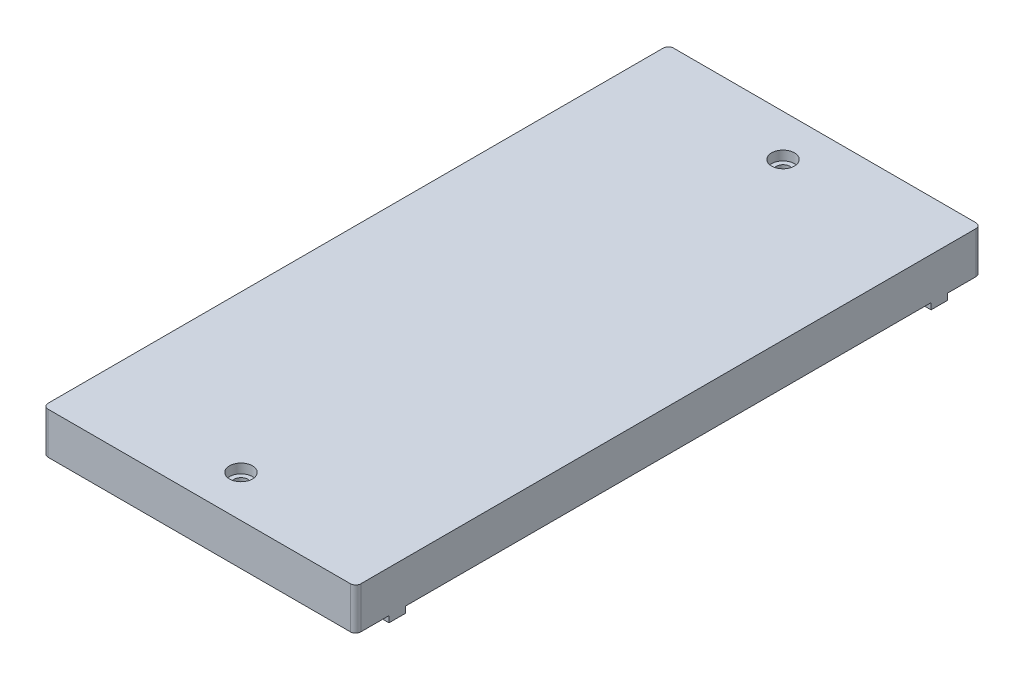
SolidWorks part; units mm, degrees
material "5052-H32"
ref_plane "Front Plane" through (0, 0, 0) normal (0, 0, 1) x (1, 0, 0)
ref_plane "Top Plane" through (0, 0, 0) normal (0, 1, 0) x (1, 0, 0)
ref_plane "Right Plane" through (0, 0, 0) normal (1, 0, 0) x (0, 0, -1)
sketch "Sketch1" plane through (0, 0, 0) normal (0, 1, 0) x (1, 0, 0)
  line L1 (75, -150) -> (-75, -150)
  line L2 (75, -150) -> (75, 150)
  line L3 (75, 150) -> (-75, 150)
  line L4 (-75, -150) -> (-75, 150)
  line L5 (75, -150) -> (-75, 150) construction
  line L6 (75, 150) -> (-75, -150) construction
  point P0 (0, 0)
  dimension "D1" = 150
  dimension "D2" = 300
extrude "Boss-Extrude1" add sketch "Sketch1" along normal blind 20
sketch "Sketch2" plane through (0, 0, 0) normal (0, 1, 0) x (1, 0, 0)
  line L0 (-75, 150) -> (-75, -150) construction
  line L1 (-75, -134) -> (75, -134)
  line L2 (-75, -134) -> (-75, -126)
  line L3 (-75, -126) -> (75, -126)
  line L4 (75, -134) -> (75, -126)
  line L5 (75, -150) -> (75, 150) construction
  line L7 (75, 134) -> (-75, 134)
  line L8 (75, 134) -> (75, 126)
  line L9 (75, 126) -> (-75, 126)
  line L10 (-75, 134) -> (-75, 126)
  point P12 (-75, -130)
  point P14 (-75, 130)
  dimension "D1" = 8
  dimension "D2" = 130
  dimension "D3" = 260
extrude "Boss-Extrude2" add sketch "Sketch2" against normal blind 3
hole_wizard "CBORE for M6 Hex Socket Thin Head Cap Screw1" positions "Sketch3" profile "Sketch4" counterbore size "M6" standard "DIN"
sketch "Sketch3" plane through (0, 20, 0) normal (0, 1, 0) x (1, 0, 0)
  point P0 (0, -130)
  point P2 (0, 130)
  dimension "D1" = 130
  dimension "D2" = 260
sketch "Sketch4" plane through (0, 20, 130) normal (1, 0, 0) x (0, 0, 1)
  line L0 (0, 0) -> (0, 24.5)
  line L1 (0, 24.5) -> (3.3, 24.5)
  line L2 (3.3, 24.5) -> (3.3, 4.5)
  line L3 (3.3, 4.5) -> (5.5, 4.5)
  line L4 (5.5, 4.5) -> (5.5, 0)
  line L5 (5.5, 0) -> (0, 0)
  line L10 (0, 24.5) -> (-3.3, 24.5) construction
  line L11 (0, -6.35) -> (0, 107.95) construction
  dimension "Hole Dia." = 6.6
  dimension "Hole Depth" = 24.5
  dimension "C'Bore Dia." = 11
  dimension "C'Bore Depth" = 4.5
  dimension "Drill Angle" = 180
hole_wizard "M8 Tapped Hole1" positions "Sketch5" profile "Sketch7" tap size "M8" standard "DIN"
sketch "Sketch5" plane through (-75, 0, 0) normal (-1, 0, 0) x (0, 0, 1)
  line L0 (-150, 20) -> (-150, 0) construction
  point P0 (0, 10)
  point P8 (-150, 10)
cosmetic thread "Hole Thread2" parameters "D1"=30, "D2"=8
sketch "Sketch7" plane through (-75, 10, 0) normal (0, 1, 0) x (0, 0, 1)
  line L0 (0, 0) -> (0, 33.75)
  line L1 (0, 33.75) -> (3.4, 33.75)
  line L2 (3.4, 33.75) -> (3.4, 0)
  line L5 (3.4, 0) -> (0, 0)
  line L10 (0, 33.75) -> (-3.4, 33.75) construction
  line L11 (0, -6.35) -> (0, 107.95) construction
  dimension "Tap Drill Dia." = 6.8
  dimension "Tap Drill Depth" = 33.75
  dimension "Drill Angle" = 180
fillet "Fillet1" radius 2.5 4 edges at (75, 10, -150) (-75, 10, -150) (-75, 10, 150) (75, 10, 150)
